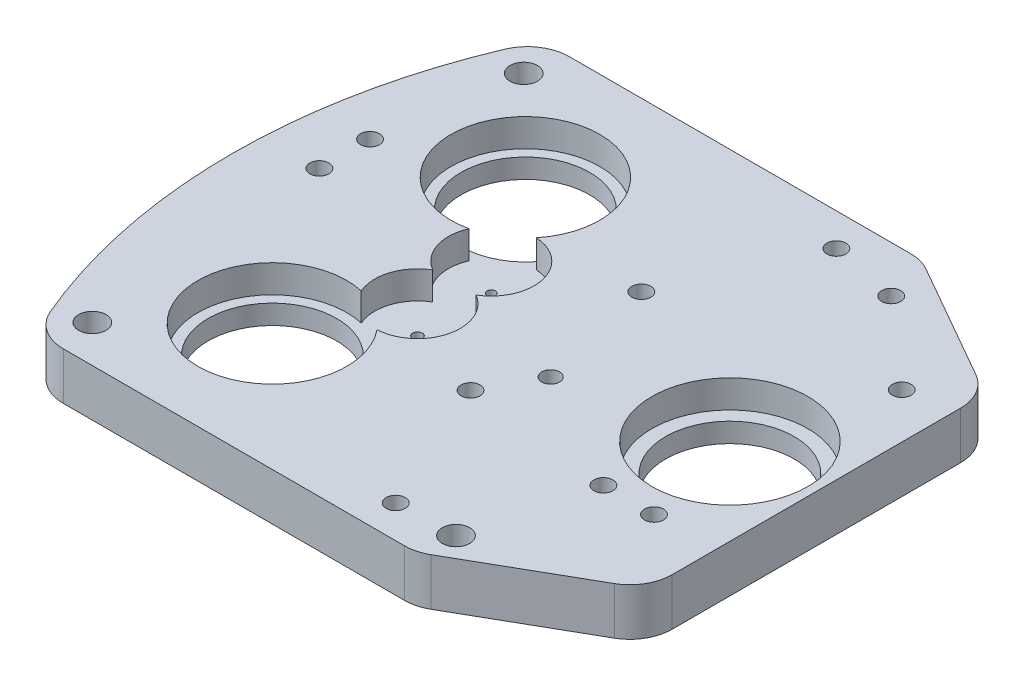
SolidWorks part; units mm, degrees
ref_plane "Front" through (0, 0, 0) normal (0, 0, 1) x (1, 0, 0)
ref_plane "Top" through (0, 0, 0) normal (0, 1, 0) x (1, 0, 0)
ref_plane "Right" through (0, 0, 0) normal (1, 0, 0) x (0, 0, -1)
sketch "Sketch1" plane through (0, 0, 0) normal (0, 1, 0) x (1, 0, 0)
  line L0 (62.5, 0) -> (-58.6146, 0) construction
  line L1 (-62.5, -60) -> (62.5, -60)
  line L2 (-62.5, -60) -> (-62.5, 60)
  line L3 (-62.5, 60) -> (62.5, 60)
  line L4 (62.5, -60) -> (62.5, 60)
  line L5 (-62.5, -60) -> (62.5, 60) construction
  line L6 (-62.5, 60) -> (62.5, -60) construction
  line L7 (-58.6146, 67.5) -> (-58.6146, -67.5) construction
  arc A0 (-58.6146, 67.5) -> (-58.6146, -67.5) centre (62.5, 0) ccw
  point P0 (0, 0)
  dimension "D1" = 125
  dimension "D2" = 120
  dimension "D3" = 135
extrude "Test_Base_Postion" add sketch "Sketch1" along normal blind 11.215 contours L2 A0 | L1 L4 L3 L2
sketch "Fingers_Position" plane through (0, 11.215, 0) normal (0, 1, 0) x (1, 0, 0)
  line L0 (-76.1542, 0) -> (62.5, 0) construction
  line L1 (-26.75, -24.75) -> (-26.75, -56.75) construction
  line L2 (-26.75, 24.75) -> (-26.75, 56.75) construction
  line L3 (-36.5, 12.5) -> (-36.5, -12.5) construction
  line L8 (5.25, -56.75) -> (-49.5, -56.75) construction
  line L9 (5.25, -56.75) -> (5.25, -24.75) construction
  line L10 (5.25, -24.75) -> (-49.5, -24.75) construction
  line L11 (-49.5, -56.75) -> (-49.5, -24.75) construction
  line L12 (5.25, -40.75) -> (-36.5, -40.75) construction
  line L13 (-21.75, -24.75) -> (-21.75, -56.75) construction
  line L14 (-36.5, -40.75) -> (-36.5, -30) construction
  line L15 (42, -29) -> (42, 0) construction
  line L16 (15.25, 44.5) -> (15.25, -10.5) construction
  line L17 (15.25, -10.5) -> (47.25, -10.5) construction
  line L18 (47.25, -10.5) -> (47.25, 44.5) construction
  line L19 (47.25, 44.5) -> (15.25, 44.5) construction
  line L20 (30, 9) -> (30, -29) construction
  line L21 (30, -29) -> (54, -29) construction
  line L22 (54, -29) -> (54, 9) construction
  line L23 (54, 9) -> (30, 9) construction
  line L24 (31.25, 44.5) -> (31.25, 0) construction
  line L25 (31.25, 0) -> (42, 0) construction
  line L26 (-21.75, 24.75) -> (-21.75, 56.75) construction
  line L27 (-49.5, 56.75) -> (-49.5, 24.75) construction
  line L28 (5.25, 24.75) -> (-49.5, 24.75) construction
  line L29 (5.25, 56.75) -> (5.25, 24.75) construction
  line L30 (5.25, 56.75) -> (-49.5, 56.75) construction
  line L31 (15.25, 17.5) -> (47.25, 17.5) construction
  line L32 (62.5, -60) -> (62.5, 60) construction
  line L33 (30, -24) -> (36, -24) construction
  line L34 (36, -24) -> (36, -29) construction
  circle A0 centre (-36.5, -30) radius 16.25 construction
  circle A1 centre (-36.5, -30) radius 17.5 construction
  circle A5 centre (-36.5, -30) radius 15 construction
  circle A6 centre (42, 0) radius 17.75 construction
  circle A7 centre (42, 0) radius 9 construction
  circle A8 centre (-23.3304, -8.75) radius 7.5 construction
  circle A9 centre (-23.3304, -8.75) radius 8.75 construction
  circle A10 centre (-23.3304, -8.75) radius 10 construction
  circle A11 centre (-23.3304, 8.75) radius 10 construction
  circle A12 centre (-23.3304, 8.75) radius 8.75 construction
  circle A13 centre (-23.3304, 8.75) radius 7.5 construction
  circle A14 centre (-36.5, 30) radius 15 construction
  circle A15 centre (-36.5, 30) radius 17.5 construction
  circle A16 centre (-36.5, 30) radius 16.25 construction
  circle A18 centre (-36.5, -30) radius 1 construction
  circle A19 centre (-36.5, 30) radius 1 construction
  arc A20 (-62.5, 60) -> (-62.5, -60) centre (62.5, 0) ccw construction
  circle A21 centre (36, -24) radius 2.25 construction
  circle A22 centre (48, -24) radius 2.25 construction
  dimension "D1" = 32.5
  dimension "D2" = 35
  dimension "D8" = 30
  dimension "D7" = 18
  dimension "D9" = 35.5
  dimension "D3" = 20
  dimension "D4" = 17.5
  dimension "D16" = 15
  dimension "D18" = 2
  dimension "D26" = 4.5
  dimension "D5" = 54.75
  dimension "D6" = 32
  dimension "D10" = 24
  dimension "D11" = 32
  dimension "D12" = 55
  dimension "D15" = 10
  dimension "D19" = 41.75
  dimension "D17" = 10.75
  dimension "D20" = 25
  dimension "D21" = 27
  dimension "D22" = 29
  dimension "D14" = 44.5
  dimension "D23" = 10.75
  dimension "D24" = 27
  dimension "D13" = 8.5
  dimension "D25" = 32
  dimension "D27" = 6
  dimension "D28" = 5
sketch "Thumb_Position" plane through (0, 11.215, 0) normal (0, 1, 0) x (1, 0, 0)
  line L12 (-76.1542, 0) -> (62.5, 0) construction
  circle A0 centre (42, 0) radius 17.75 construction
  circle A1 centre (42, 0) radius 9 construction
  dimension "D1" = 18
  dimension "D2" = 35.5
sketch "Intermediate_Gear_Position" plane through (0, 11.215, 0) normal (0, 1, 0) x (1, 0, 0)
  line L0 (-62.75, 25.4139) -> (-62.75, 19.4139) construction
  line L1 (-29.75, 25.4139) -> (-29.75, 1.4139) construction
  line L2 (-29.75, 25.4139) -> (-67.75, 25.4139) construction
  line L3 (-67.75, 25.4139) -> (-67.75, 1.4139) construction
  line L4 (-29.75, 1.4139) -> (-67.75, 1.4139) construction
  line L5 (-67.75, 13.4139) -> (-38.75, 13.4139) construction
  line L6 (-26.75, 24.75) -> (-26.75, 56.75) construction
  line L7 (-62.75, 19.4139) -> (-67.75, 19.4139) construction
  circle A3 centre (-23.3304, -8.75) radius 14 construction
  circle A6 centre (-38.75, 13.4139) radius 13 construction
  circle A7 centre (-62.75, 19.4139) radius 2.25 construction
  circle A8 centre (-62.75, 7.4139) radius 2.25 construction
  dimension "D6" = 28
  dimension "D11" = 26
  dimension "D5" = 4.5
  dimension "D1" = 24
  dimension "D2" = 38
  dimension "D4" = 29
  dimension "D3" = 3
  dimension "D7" = 6
  dimension "D8" = 5
sketch "Sketch10" plane through (0, 11.215, 0) normal (0, 1, 0) x (1, 0, 0)
  circle A0 centre (-36.5, 30) radius 15.25
  circle A1 centre (-36.5, -30) radius 15.25
  circle A2 centre (42, 0) radius 15.25
  dimension "D1" = 30.5
extrude "Connect_Finger_Holes" cut sketch "Sketch10" against normal through all
sketch "Sketch11" plane through (0, 11.215, 0) normal (0, 1, 0) x (1, 0, 0)
  circle A0 centre (42, 0) radius 18.5
  dimension "D1" = 37
extrude "XL320_Finger_Knuckle_Mount" cut sketch "Sketch11" against normal blind 6.6025
sketch "Sketch24" plane through (0, 11.215, 0) normal (0, 1, 0) x (1, 0, 0)
  line L0 (5.25, -24.75) -> (5.25, -20.25) construction
  line L1 (5.25, -20.25) -> (0.75, -20.25) construction
  line L2 (15, -56.75) -> (5.25, -56.75) construction
  line L3 (5.25, -56.75) -> (-49.5, -56.75) construction
  line L4 (15, -56.75) -> (15, -52.25) construction
  line L5 (5.25, 24.75) -> (5.25, 20.25) construction
  line L6 (5.25, 20.25) -> (0.75, 20.25) construction
  line L7 (15, 56.75) -> (5.25, 56.75) construction
  line L8 (5.25, 56.75) -> (-49.5, 56.75) construction
  line L9 (15, 56.75) -> (15, 52.25) construction
  line L10 (47.25, 44.5) -> (51.75, 44.5) construction
  line L11 (51.75, 44.5) -> (51.75, 31) construction
  line L12 (31.25, 44.5) -> (31.25, 49) construction
  line L13 (47.25, 44.5) -> (15.25, 44.5) construction
  circle A0 centre (15, 52.25) radius 2.25
  circle A1 centre (0.75, 20.25) radius 2.25
  circle A2 centre (0.75, -20.25) radius 2.25
  circle A3 centre (15, -52.25) radius 2.25
  circle A4 centre (51.75, 31) radius 2.25
  circle A5 centre (31.25, 49) radius 2.25
  dimension "D2" = 4.5
  dimension "D1" = 4.5
  dimension "D3" = 4.5
  dimension "D4" = 13.5
  dimension "D5" = 9.75
  dimension "D6" = 9.75
extrude "AX12_Mount_Holes_(M4)" cut sketch "Sketch24" against normal through all
sketch "Sketch21" plane through (0, 11.215, 0) normal (0, 1, 0) x (1, 0, 0)
  circle A0 centre (-36.5, 30) radius 17.65
  circle A1 centre (-23.3304, 8.75) radius 10.15
  circle A2 centre (-23.3304, -8.75) radius 10.15
  circle A3 centre (-36.5, -30) radius 17.65
  dimension "D1" = 20.3
  dimension "D2" = 35.3
extrude "Gears_Holes" cut sketch "Sketch21" against normal blind 6.6025 contours A0 | A1 | A2 | A3
sketch "Sketch22" plane through (0, 4.6125, 0) normal (0, 1, 0) x (1, 0, 0)
  circle A1 centre (-23.3304, -8.75) radius 1.15
  dimension "D1" = 2.3
extrude "Gears_Rod_Holes" cut sketch "Sketch22" against normal blind 3
sketch "Sketch28" plane through (0, 4.6125, 0) normal (0, 1, 0) x (1, 0, 0)
  circle A0 centre (-23.3304, 8.75) radius 1
  dimension "D1" = 2
sketch "Sketch29" plane through (0, 11.215, 0) normal (0, 1, 0) x (1, 0, 0)
  line L0 (27.5, 60) -> (62.5, 40)
  line L1 (-62.5, 60) -> (62.5, 60) construction
  line L2 (62.5, -60) -> (62.5, 60) construction
  line L3 (62.5, 40) -> (62.5, 60)
  line L4 (62.5, 60) -> (27.5, 60)
  line L5 (62.5, 0) -> (-76.1542, 0) construction
  line L6 (62.5, -60) -> (27.5, -60)
  line L7 (62.5, -40) -> (62.5, -60)
  line L8 (27.5, -60) -> (62.5, -40)
  dimension "D1" = 35
  dimension "D2" = 20
extrude "Cut-Extrude1" cut sketch "Sketch29" against normal through all
fillet "Fillet1" radius 10 6 edges at (-62.5, 5.6075, 60) (27.5, 5.6075, 60) (62.5, 5.6075, 40) (62.5, 5.6075, -40) (27.5, 5.6075, -60) (-62.5, 5.6075, -60)
sketch "Sketch17" plane through (0, 11.215, 0) normal (0, 1, 0) x (1, 0, 0)
  line L0 (-58.0408, 51.1529) -> (-61.5696, 58.3326) construction
  line L3 (-76.1542, 0) -> (62.5, 0) construction
  line L4 (-56.0408, 60) -> (-56.0408, -60) construction
  line L6 (-58.0408, 51.1529) -> (-56.0408, 51.1529) construction
  line L7 (24.8444, -60) -> (24.8444, 60) construction
  line L8 (28.8444, -51.7944) -> (24.8444, -51.7944) construction
  line L9 (28.8444, -51.7944) -> (27.411, -59.665) construction
  circle A0 centre (-58.0408, 51.1529) radius 3.25
  circle A1 centre (-58.0408, -51.1529) radius 3.25
  circle A2 centre (28.8444, -51.7944) radius 3.25
  arc A3 (-56.0408, 60) -> (-65.2547, 53.8864) centre (-56.0408, 50) ccw construction
  arc A4 (24.8444, -60) -> (29.8057, -58.6824) centre (24.8444, -50) ccw construction
  dimension "D3" = 6.5
  dimension "D1" = 6.5
  dimension "D2" = 8
  dimension "D4" = 2
  dimension "D5" = 8
  dimension "D6" = 4
extrude "Connect_Holes_(M6)" cut sketch "Sketch17" against normal through all
sketch "Sketch19" plane through (0, 0, 0) normal (0, -1, 0) x (1, 0, 0)
  line L0 (-58.0408, 51.1529) -> (-58.0408, 57.2151) construction
  line L1 (-58.0408, 51.1529) -> (-63.2908, 54.184) construction
  line L2 (-58.0408, 51.1529) -> (-52.7908, 54.184) construction
  line L3 (-58.0408, 51.1529) -> (-63.2908, 48.1218) construction
  line L4 (-58.0408, 51.1529) -> (-52.7908, 48.1218) construction
  line L5 (-58.0408, 51.1529) -> (-58.0408, 45.0908) construction
  line L6 (-58.0408, 57.2151) -> (-63.2908, 54.184)
  line L7 (-63.2908, 54.184) -> (-63.2908, 48.1218)
  line L8 (-63.2908, 48.1218) -> (-58.0408, 45.0908)
  line L9 (-58.0408, 45.0908) -> (-52.7908, 48.1218)
  line L10 (-52.7908, 48.1218) -> (-52.7908, 54.184)
  line L11 (-52.7908, 54.184) -> (-58.0408, 57.2151)
  line L12 (28.8444, 45.7323) -> (34.0944, 48.7634)
  line L13 (28.8444, 51.7944) -> (23.5944, 48.7634) construction
  line L14 (34.0944, 48.7634) -> (34.0944, 54.8255)
  line L15 (34.0944, 54.8255) -> (28.8444, 57.8566)
  line L16 (23.5944, 54.8255) -> (23.5944, 48.7634)
  line L17 (28.8444, 51.7944) -> (34.0944, 48.7634) construction
  line L24 (-58.0408, -51.1529) -> (-52.7908, -54.184) construction
  line L25 (-58.0408, -51.1529) -> (-63.2908, -48.1218) construction
  line L26 (-63.2908, -48.1218) -> (-63.2908, -54.184)
  line L27 (-52.7908, -48.1218) -> (-58.0408, -45.0908)
  line L28 (-58.0408, -51.1529) -> (-52.7908, -48.1218) construction
  line L29 (-58.0408, -51.1529) -> (-63.2908, -54.184) construction
  line L36 (28.8444, 51.7944) -> (28.8444, 57.8566) construction
  line L37 (28.8444, 51.7944) -> (23.5944, 54.8255) construction
  line L38 (23.5944, 48.7634) -> (28.8444, 45.7323)
  line L39 (28.8444, 51.7944) -> (28.8444, 45.7323) construction
  line L40 (28.8444, 57.8566) -> (23.5944, 54.8255)
  line L41 (28.8444, 51.7944) -> (34.0944, 54.8255) construction
  line L42 (-63.2908, -54.184) -> (-58.0408, -57.2151)
  line L43 (-58.0408, -57.2151) -> (-52.7908, -54.184)
  line L44 (-58.0408, -51.1529) -> (-58.0408, -45.0908) construction
  line L45 (-58.0408, -45.0908) -> (-63.2908, -48.1218)
  line L46 (-58.0408, -51.1529) -> (-58.0408, -57.2151) construction
  line L47 (-52.7908, -54.184) -> (-52.7908, -48.1218)
  circle A0 centre (-58.0408, 51.1529) radius 5.25 construction
  circle A3 centre (28.8444, 51.7944) radius 5.25 construction
  circle A4 centre (28.8444, 51.7944) radius 3.25 construction
  circle A5 centre (-58.0408, -51.1529) radius 5.25 construction
  circle A6 centre (-58.0408, -51.1529) radius 3.25 construction
  point P27 (-64.0933, -33.4148)
  dimension "D1" = 10.5
  dimension "D4" = 10.5
  dimension "D7" = 10.5
  dimension "D2" = 60
  dimension "D3" = 60
  dimension "D5" = 60
  dimension "D6" = 60
  dimension "D8" = 60
  dimension "D9" = 60
extrude "Nuts_(M6)" cut sketch "Sketch19" against normal blind 6
sketch "Sketch27" plane through (0, 0, 0) normal (0, -1, 0) x (1, 0, 0)
  line L0 (15, 56.5801) -> (11.25, 54.4151)
  line L1 (11.25, 54.4151) -> (11.25, 50.0849)
  line L2 (11.25, 50.0849) -> (15, 47.9199)
  line L3 (15, 47.9199) -> (18.75, 50.0849)
  line L4 (18.75, 50.0849) -> (18.75, 54.4151)
  line L5 (18.75, 54.4151) -> (15, 56.5801)
  line L6 (11.25, 54.4151) -> (18.75, 50.0849) construction
  line L7 (11.25, 50.0849) -> (18.75, 54.4151) construction
  line L8 (15, 56.5801) -> (15, 47.9199) construction
  line L11 (-3, 22.4151) -> (-3, 18.0849)
  line L12 (4.5, 18.0849) -> (4.5, 22.4151)
  line L15 (0.75, 15.9199) -> (4.5, 18.0849)
  line L20 (0.75, 24.5801) -> (0.75, 15.9199) construction
  line L24 (-3, 22.4151) -> (4.5, 18.0849) construction
  line L26 (-3, 18.0849) -> (0.75, 15.9199)
  line L27 (4.5, 22.4151) -> (0.75, 24.5801)
  line L28 (-3, 18.0849) -> (4.5, 22.4151) construction
  line L30 (0.75, 24.5801) -> (-3, 22.4151)
  line L38 (-3, -18.0849) -> (4.5, -22.4151) construction
  line L40 (-3, -22.4151) -> (0.75, -24.5801)
  line L44 (0.75, -24.5801) -> (4.5, -22.4151)
  line L45 (-3, -18.0849) -> (-3, -22.4151)
  line L46 (-3, -22.4151) -> (4.5, -18.0849) construction
  line L53 (4.5, -18.0849) -> (0.75, -15.9199)
  line L54 (0.75, -15.9199) -> (-3, -18.0849)
  line L55 (4.5, -22.4151) -> (4.5, -18.0849)
  line L56 (0.75, -15.9199) -> (0.75, -24.5801) construction
  line L57 (11.25, -54.4151) -> (18.75, -50.0849) construction
  line L58 (11.25, -50.0849) -> (11.25, -54.4151)
  line L59 (11.25, -54.4151) -> (15, -56.5801)
  line L60 (18.75, -50.0849) -> (15, -47.9199)
  line L61 (15, -47.9199) -> (11.25, -50.0849)
  line L62 (15, -56.5801) -> (18.75, -54.4151)
  line L63 (11.25, -50.0849) -> (18.75, -54.4151) construction
  line L64 (15, -47.9199) -> (15, -56.5801) construction
  line L65 (18.75, -54.4151) -> (18.75, -50.0849)
  line L66 (55.5, -28.8349) -> (51.75, -26.6699)
  line L67 (51.75, -26.6699) -> (51.75, -35.3301) construction
  line L68 (48, -33.1651) -> (55.5, -28.8349) construction
  line L69 (48, -28.8349) -> (55.5, -33.1651) construction
  line L70 (48, -28.8349) -> (48, -33.1651)
  line L71 (51.75, -26.6699) -> (48, -28.8349)
  line L72 (48, -33.1651) -> (51.75, -35.3301)
  line L73 (55.5, -33.1651) -> (55.5, -28.8349)
  line L74 (51.75, -35.3301) -> (55.5, -33.1651)
  line L75 (27.5, -46.8349) -> (27.5, -51.1651)
  line L76 (27.5, -51.1651) -> (31.25, -53.3301)
  line L77 (35, -51.1651) -> (35, -46.8349)
  line L78 (35, -46.8349) -> (31.25, -44.6699)
  line L79 (27.5, -51.1651) -> (35, -46.8349) construction
  line L80 (31.25, -53.3301) -> (35, -51.1651)
  line L81 (31.25, -44.6699) -> (31.25, -53.3301) construction
  line L82 (27.5, -46.8349) -> (35, -51.1651) construction
  line L83 (31.25, -44.6699) -> (27.5, -46.8349)
  circle A0 centre (15, 52.25) radius 3.75 construction
  circle A1 centre (0.75, 20.25) radius 3.75 construction
  circle A3 centre (0.75, 20.25) radius 2.25 construction
  circle A5 centre (0.75, -20.25) radius 3.75 construction
  circle A7 centre (0.75, -20.25) radius 2.25 construction
  circle A9 centre (15, -52.25) radius 3.75 construction
  circle A11 centre (15, 52.25) radius 2.25 construction
  circle A17 centre (15, -52.25) radius 2.25 construction
  circle A18 centre (51.75, -31) radius 3.75 construction
  circle A19 centre (51.75, -31) radius 2.25 construction
  circle A20 centre (31.25, -49) radius 3.75 construction
  circle A21 centre (31.25, -49) radius 2.25 construction
  dimension "D1" = 7.5
  dimension "D3" = 7.5
  dimension "D5" = 7.5
  dimension "D7" = 7.5
  dimension "D9" = 7.5
  dimension "D11" = 7.5
  dimension "D2" = 60
  dimension "D4" = 60
  dimension "D6" = 60
  dimension "D8" = 60
  dimension "D10" = 60
  dimension "D12" = 60
extrude "Nuts_(M4)" cut sketch "Sketch27" against normal blind 5
sketch "Sketch30" plane through (0, 11.215, 0) normal (0, 1, 0) x (1, 0, 0)
  line L0 (62.5, 0) -> (2.5, 0) construction
  line L1 (2.5, 0) -> (2.5, -8) construction
  line L2 (2.5, -8) -> (7.5, -8) construction
  circle A2 centre (7.5, -8) radius 2.1
  dimension "D1" = 8
  dimension "D3" = 5
  dimension "D4" = 4.2
  dimension "D2" = 60
extrude "Connect_To_House" cut sketch "Sketch30" against normal through all
sketch "Sketch31" plane through (0, 11.215, 0) normal (0, 1, 0) x (1, 0, 0)
  circle A0 centre (-62.75, 19.4139) radius 2.25
  circle A1 centre (-62.75, 7.4139) radius 2.25
  circle A2 centre (36, -24) radius 2.25
  circle A3 centre (48, -24) radius 2.25
  dimension "D1" = 4.5
extrude "M4_Extension_Hole" cut sketch "Sketch31" against normal blind 5
extrude "M2_Shaft_Hole" cut sketch "Sketch28" against normal blind 3
equation "\"od1\"= 35'outside diameter finger"
equation "\"n1\"= 26'number of teeth finger"
equation "\"m1\"= \"od1\" / ( \"n1\" + 2 )'module finger"
equation "\"p1\"= \"m1\" * pi'pitch finger"
equation "\"d1\"= \"m1\" * \"n1\"'primitive diameter finger"
equation "\"da1\"= \"d1\" + 2 * \"m1\"'head diamater finger"
equation "\"df1\"= \"d1\" - 2 * \"m1\"'foot diameter finger"
equation "\"od2\"= 20'outside diameter intermediate"
equation "\"n2\"= 14'number of teeth intermediate"
equation "\"m2\"= \"od2\" / ( \"n2\" + 2 )'module intermediate"
equation "\"p2\"= \"m2\" * pi'pitch intermediate"
equation "\"d2\"= \"m2\" * \"n2\"'primitive diameter intermediate"
equation "\"da2\"= \"d2\" + 2 * \"m2\"'head diamater intermediate"
equation "\"df2\"= \"d2\" - 2 * \"m2\"'foot diameter intermediate"
equation "\"od3\"= 30'outside diameter top"
equation "\"n3\"= 28'number of teeth top"
equation "\"m3\"= \"od3\" / ( \"n3\" + 2 )'module top"
equation "\"p3\"= \"m3\" * pi'pitch top"
equation "\"d3\"= \"m3\" * \"n3\"'primitive diameter top"
equation "\"da3\"= \"d3\" + 2 * \"m3\"'head diamater top"
equation "\"df3\"= \"d3\" - 2 * \"m3\"'foot diameter top"
equation "\"od4\"= 28'outside diameter drive"
equation "\"n4\"= 26'number of teeth drive"
equation "\"m4\"= \"od4\" / ( \"n4\" + 2 )'module drive"
equation "\"p4\"= \"m4\" * pi'pitch drive"
equation "\"d4\"= \"m4\" * \"n4\"'primitive diameter drive"
equation "\"da4\"= \"d4\" + 2 * \"m4\"'head diamater drive"
equation "\"df4\"= \"d4\" - 2 * \"m4\"'foot diameter drive"
equation "\"D2@Fingers_Position\"=\"da1\""
equation "\"D1@Fingers_Position\"=\"d1\""
equation "\"D8@Fingers_Position\"=\"df1\""
equation "\"D3@Fingers_Position\"=\"da2\""
equation "\"D4@Fingers_Position\"=\"d2\""
equation "\"D6@Intermediate_Gear_Position\"=\"d3\""
equation "\"D16@Fingers_Position\"=\"df2\""
equation "\"D11@Intermediate_Gear_Position\"=\"d4\""
